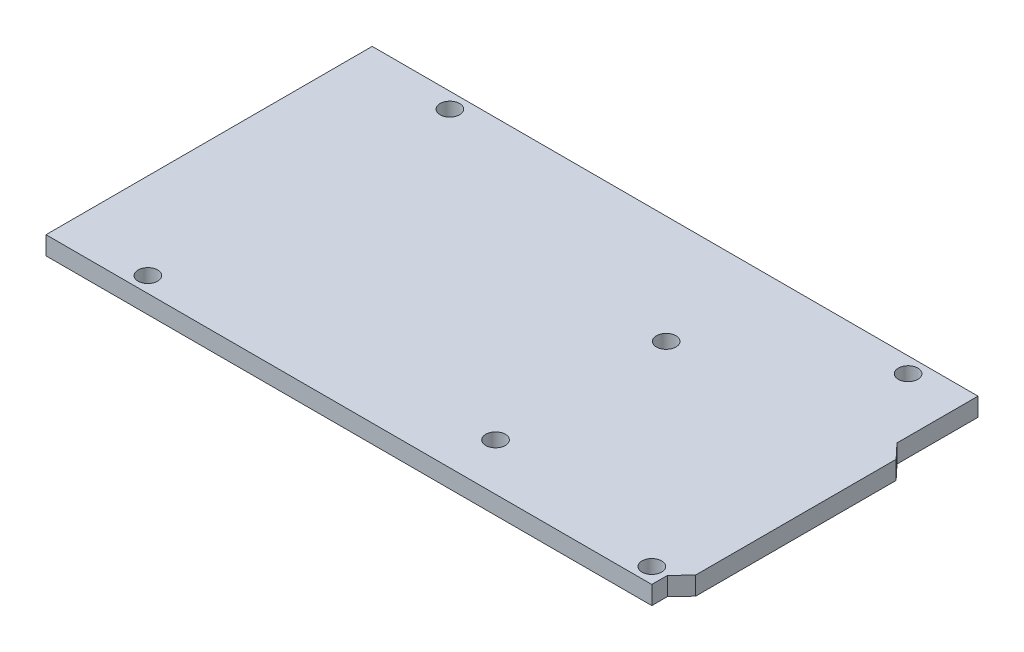
SolidWorks part; units mm, degrees
ref_plane "Front Plane" through (0, 0, 0) normal (0, 0, 1) x (1, 0, 0)
ref_plane "Top Plane" through (0, 0, 0) normal (0, 1, 0) x (1, 0, 0)
ref_plane "Right Plane" through (0, 0, 0) normal (1, 0, 0) x (0, 0, -1)
sketch "Sketch1" plane through (0, 0, 0) normal (0, 1, 0) x (1, 0, 0)
  line L0 (49.53, -24.13) -> (51.78, -21.74)
  line L1 (-49.53, 26.67) -> (49.53, 26.67)
  line L2 (-49.53, 26.67) -> (-49.53, -26.67)
  line L3 (-49.53, -26.67) -> (49.53, -26.67)
  line L4 (49.53, 26.67) -> (49.53, 13.42)
  line L5 (-49.53, 26.67) -> (49.53, -26.67) construction
  line L6 (-49.53, -26.67) -> (49.53, 26.67) construction
  line L7 (51.78, -21.74) -> (51.78, 11.03)
  line L8 (51.78, 11.03) -> (49.53, 13.42)
  line L9 (49.53, -24.13) -> (49.53, -26.67)
  circle A1 centre (-34.29, 24.13) radius 1.5993
  circle A2 centre (40.64, 24.13) radius 1.6
  circle A3 centre (46.99, -24.13) radius 1.6
  circle A4 centre (-35.41, -24.13) radius 1.6
  circle A5 centre (16.28, 8.93) radius 1.6
  circle A6 centre (16.28, -18.97) radius 1.6
  point P0 (0, 0)
  point P18 (0, 0)
  point P22 (49.53, -25.4)
  dimension "D3" = 3.1986
  dimension "D4" = 3.2
  dimension "D12" = 3.2
  dimension "D13" = 3.2
  dimension "D18" = 3.2
  dimension "D19" = 3.2
  dimension "D1" = 99.06
  dimension "D2" = 53.34
  dimension "D5" = 74.93
  dimension "D6" = 15.24
  dimension "D7" = 2.54
  dimension "D8" = 2.25
  dimension "D9" = 32.77
  dimension "D10" = 37.55
  dimension "D11" = 2.54
  dimension "D14" = 2.54
  dimension "D15" = 2.54
  dimension "D16" = 82.4
  dimension "D17" = 27.9
  dimension "D20" = 7.7
  dimension "D21" = 35.5
extrude "Boss-Extrude1" add sketch "Sketch1" along normal blind 3
